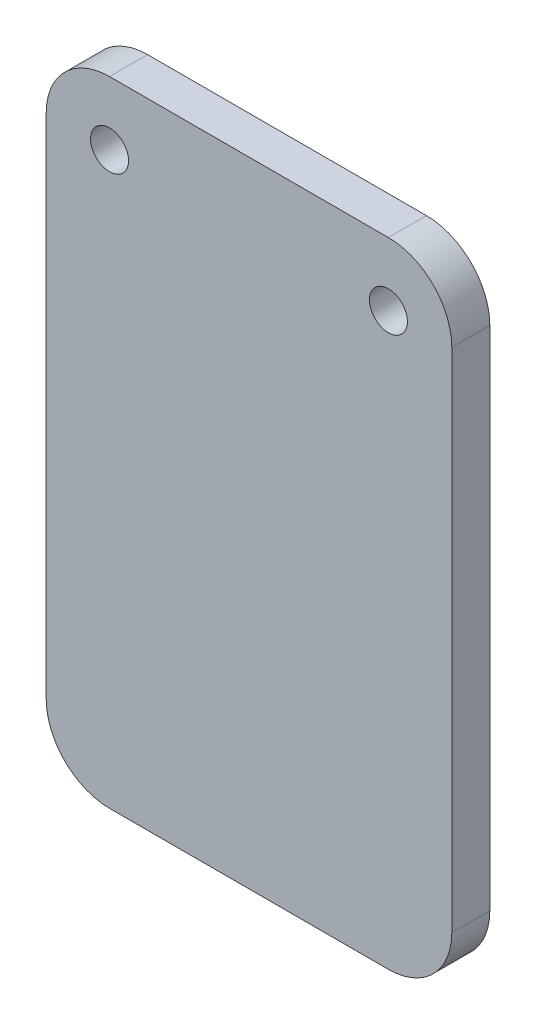
SolidWorks part; units mm, degrees
ref_plane "Front Plane" through (0, 0, 0) normal (0, 0, 1) x (1, 0, 0)
ref_plane "Top Plane" through (0, 0, 0) normal (0, 1, 0) x (1, 0, 0)
ref_plane "Right Plane" through (0, 0, 0) normal (1, 0, 0) x (0, 0, -1)
sketch "Sketch1" plane through (0, 0, 0) normal (0, 0, 1) x (1, 0, 0)
  line L0 (16, 50) -> (16, 0) construction
  line L1 (5, 0) -> (27, 0)
  line L2 (0, 5) -> (0, 45)
  line L3 (5, 50) -> (27, 50)
  line L4 (32, 5) -> (32, 45)
  line L5 (32, 25) -> (16, 25) construction
  arc A0 (27, 50) -> (32, 45) centre (27, 45) cw
  arc A1 (27, 0) -> (32, 5) centre (27, 5) ccw
  arc A2 (5, 0) -> (0, 5) centre (5, 5) cw
  arc A3 (0, 45) -> (5, 50) centre (5, 45) cw
  circle A4 centre (5, 45) radius 1.5
  circle A8 centre (27, 45) radius 1.5
  point P7 (32, 50)
  point P10 (32, 0)
  point P13 (0, 0)
  point P30 (25, 25)
  dimension "D3" = 5
  dimension "D4" = 3
  dimension "D1" = 32
  dimension "D2" = 50
extrude "Boss-Extrude1" add sketch "Sketch1" along normal blind 3
sketch "Sketch2" plane through (0, 0, 3) normal (0, 0, 1) x (1, 0, 0)
  line L0 (16, 0) -> (16, 50) construction
  line L1 (5, 0) -> (27, 0) construction
  line L2 (27, 50) -> (5, 50) construction
  line L3 (32, 25) -> (0, 25) construction
  line L4 (32, 5) -> (32, 45) construction
  line L5 (0, 45) -> (0, 5) construction
